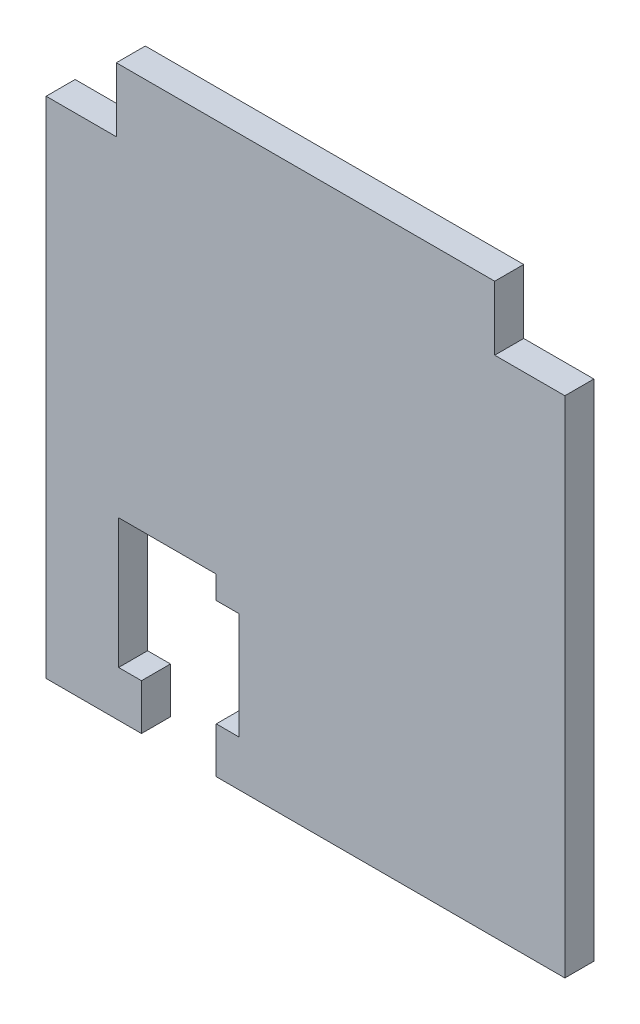
SolidWorks part; units mm, degrees
ref_plane "Plan de face" through (0, 0, 0) normal (0, 0, 1) x (1, 0, 0)
ref_plane "Plan de dessus" through (0, 0, 0) normal (0, 1, 0) x (1, 0, 0)
ref_plane "Plan de droite" through (0, 0, 0) normal (1, 0, 0) x (0, 0, -1)
sketch "Esquisse1" plane through (0, 0, 0) normal (0, 0, 1) x (1, 0, 0)
  line L1 (-170, -186.25) -> (170, -186.25)
  line L2 (-170, -186.25) -> (-170, 186.25)
  line L3 (-170, 186.25) -> (170, 186.25)
  line L4 (170, -186.25) -> (170, 186.25)
  line L5 (-170, -186.25) -> (170, 186.25) construction
  line L6 (-170, 186.25) -> (170, -186.25) construction
  point P0 (0, 0)
  dimension "D1" = 340
  dimension "D2" = 372.5
extrude "Boss.-Extru.1" add sketch "Esquisse1" along normal blind 19
sketch "Esquisse2" plane through (0, 0, 19) normal (0, 0, 1) x (1, 0, 0)
  line L0 (-124, 186.25) -> (-124, 144.25)
  line L1 (170, 186.25) -> (-170, 186.25) construction
  line L2 (-124, 144.25) -> (-170, 144.25)
  line L3 (-170, 186.25) -> (-170, -186.25) construction
  line L4 (124, 186.25) -> (124, 144.25)
  line L5 (124, 144.25) -> (170, 144.25)
  line L6 (170, -186.25) -> (170, 186.25) construction
  line L7 (-124, 186.25) -> (-170, 186.25)
  line L8 (-170, 186.25) -> (-170, 144.25)
  line L9 (124, 186.25) -> (170, 186.25)
  line L10 (170, 186.25) -> (170, 144.25)
  dimension "D1" = 42
  dimension "D2" = 46
  dimension "D3" = 42
  dimension "D4" = 46
extrude "Enlèv. mat.-Extru.1" cut sketch "Esquisse2" against normal through all
sketch "Esquisse3" plane through (0, 0, 19) normal (0, 0, 1) x (1, 0, 0)
  line L0 (-170, 144.25) -> (-170, -186.25) construction
  line L1 (170, -186.25) -> (170, 144.25) construction
  line L2 (-75, -81.25) -> (75, -81.25)
  line L3 (-75, -81.25) -> (-75, 68.75)
  line L4 (-75, 68.75) -> (75, 68.75)
  line L5 (75, -81.25) -> (75, 68.75)
  line L6 (-75, -81.25) -> (75, 68.75) construction
  line L7 (-75, 68.75) -> (75, -81.25) construction
  line L8 (-170, -186.25) -> (170, -186.25) construction
  line L9 (-170, 144.25) -> (-124, 144.25) construction
  circle A3 centre (-75, 68.75) radius 7.4706
  circle A4 centre (75, 68.75) radius 5.3217
  circle A5 centre (75, -81.25) radius 2.514
  circle A6 centre (-75, -81.25) radius 5.7111
  point P10 (0, -6.25)
  dimension "D1" = 95
  dimension "D2" = 95
  dimension "D3" = 105
  dimension "D4" = 150
  dimension "D5" = 150
  dimension "D6" = 75.5
sketch "Esquisse4" plane through (0, 0, 19) normal (0, 0, 1) x (1, 0, 0)
  line L0 (-122.5, -186.25) -> (-122.5, -171.25) construction
  line L1 (-170, -186.25) -> (170, -186.25) construction
  line L2 (-122.5, -171.25) -> (-170, -171.25) construction
  line L3 (-170, 144.25) -> (-170, -186.25) construction
  line L5 (-122.5, -171.25) -> (-43.5, -171.25)
  line L6 (-122.5, -171.25) -> (-122.5, -71.25)
  line L7 (-122.5, -71.25) -> (-43.5, -71.25)
  line L8 (-43.5, -171.25) -> (-43.5, -71.25)
  dimension "D1" = 47.5
  dimension "D2" = 15
  dimension "D3" = 100
  dimension "D4" = 79
extrude "Enlèv. mat.-Extru.2" cut sketch "Esquisse4" against normal blind 30
sketch "Esquisse5" plane through (0, 0, 19) normal (0, 0, 1) x (1, 0, 0)
  line L0 (-122.5, -71.25) -> (-122.5, -171.25) construction
  line L1 (-43.5, -171.25) -> (-58.5, -171.25)
  line L2 (-43.5, -171.25) -> (-43.5, -156.25)
  line L3 (-43.5, -156.25) -> (-58.5, -156.25)
  line L4 (-58.5, -171.25) -> (-58.5, -156.25)
  line L5 (-122.5, -171.25) -> (-107.5, -171.25)
  line L6 (-122.5, -171.25) -> (-122.5, -156.25)
  line L7 (-122.5, -156.25) -> (-107.5, -156.25)
  line L8 (-107.5, -171.25) -> (-107.5, -156.25)
  line L9 (-122.5, -171.25) -> (-43.5, -171.25) construction
  line L11 (-43.5, -71.25) -> (-58.5, -71.25)
  line L12 (-43.5, -71.25) -> (-43.5, -86.25)
  line L13 (-43.5, -86.25) -> (-58.5, -86.25)
  line L14 (-58.5, -71.25) -> (-58.5, -86.25)
  dimension "D1" = 15
  dimension "D2" = 15
  dimension "D3" = 15
  dimension "D4" = 15
  dimension "D5" = 15
  dimension "D6" = 15
extrude "Boss.-Extru.2" add sketch "Esquisse5" against normal up to vertex (19 mm away)
sketch "Esquisse6" plane through (0, 0, 19) normal (0, 0, 1) x (1, 0, 0)
  line L0 (-107.5, -171.25) -> (-107.5, -186.25)
  line L1 (-170, -186.25) -> (170, -186.25) construction
  line L2 (-107.5, -186.25) -> (-58.5, -186.25)
  line L3 (-58.5, -186.25) -> (-58.5, -171.25)
  line L4 (-58.5, -171.25) -> (-107.5, -171.25)
extrude "Enlèv. mat.-Extru.3" cut sketch "Esquisse6" against normal blind 20
